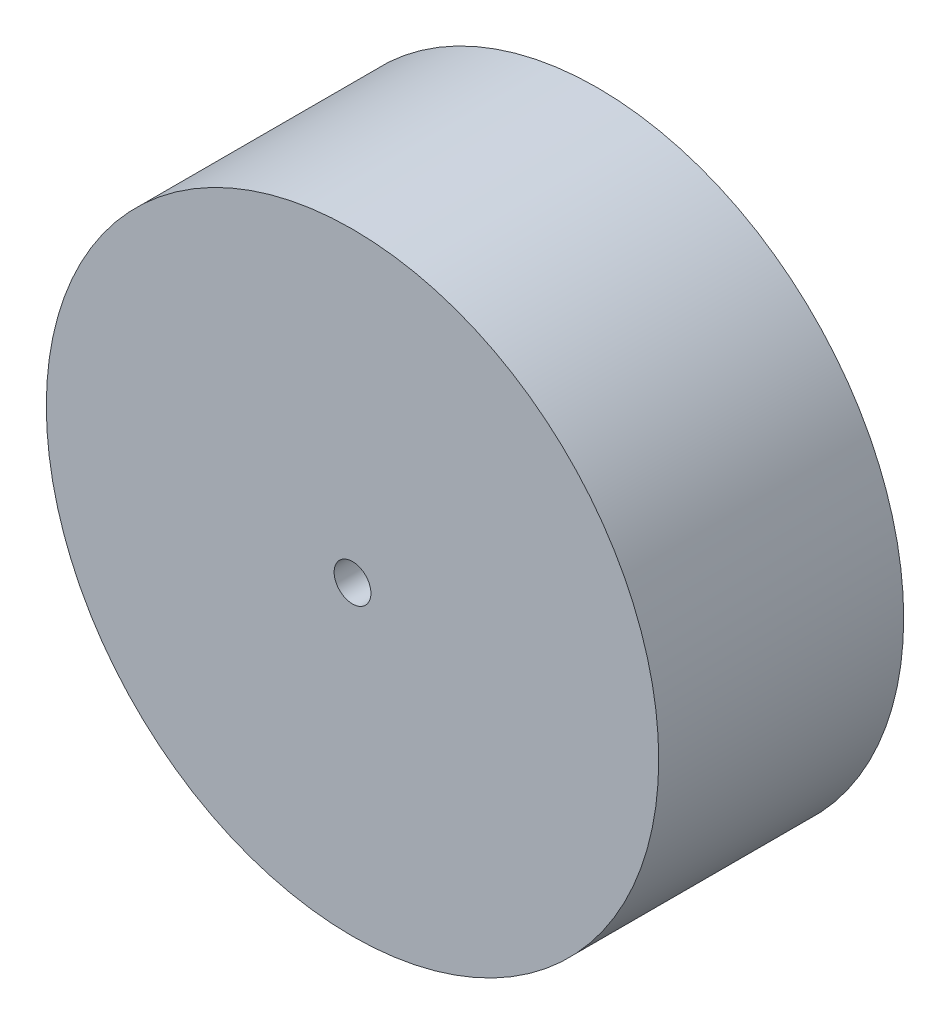
SolidWorks part; units mm, degrees
ref_plane "Front Plane" through (0, 0, 0) normal (0, 0, 1) x (1, 0, 0)
ref_plane "Top Plane" through (0, 0, 0) normal (0, 1, 0) x (1, 0, 0)
ref_plane "Right Plane" through (0, 0, 0) normal (1, 0, 0) x (0, 0, -1)
sketch "Sketch1" plane through (0, 0, 0) normal (0, 0, 1) x (1, 0, 0)
  circle A0 centre (0, 0) radius 50
  dimension "D1" = 100
extrude "Boss-Extrude1" add sketch "Sketch1" along normal blind 40
sketch "Sketch2" plane through (0, 0, 0) normal (0, 0, -1) x (-1, 0, 0)
  circle A0 centre (0, 0) radius 3
  dimension "D1" = 6
extrude "Cut-Extrude2" cut sketch "Sketch2" against normal blind 50
